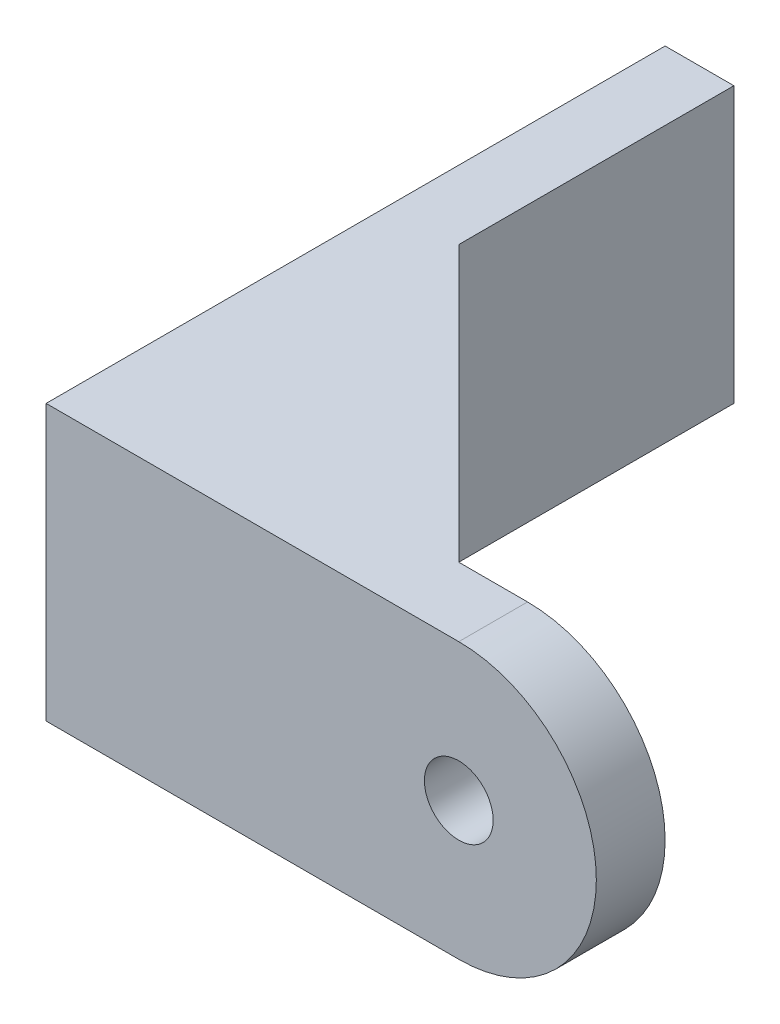
SolidWorks part; units mm, degrees
material "Custom Plastic"
ref_plane "Front Plane" through (0, 0, 0) normal (0, 0, 1) x (1, 0, 0)
ref_plane "Top Plane" through (0, 0, 0) normal (0, 1, 0) x (1, 0, 0)
ref_plane "Right Plane" through (0, 0, 0) normal (1, 0, 0) x (0, 0, -1)
sketch "Sketch1" plane through (0, 0, 0) normal (0, 0, 1) x (1, 0, 0)
  line L0 (-15, -10) -> (-15, 10)
  line L1 (-15, -10) -> (15, -10)
  line L2 (-15, 10) -> (15, 10)
  line L4 (0, 10) -> (0, -10) construction
  line L5 (-15, 0) -> (15, 0) construction
  line L6 (15, 0) -> (15, -10)
  arc A0 (15, 10) -> (15, -10) centre (15, 0) cw
  circle A1 centre (15, 0) radius 2.5
  point P1 (0, 0)
  dimension "D3" = 5
  dimension "D1" = 20
  dimension "D2" = 30
extrude "Boss-Extrude1" add sketch "Sketch1" along normal blind 5
sketch "Sketch2" plane through (0, 0, 0) normal (0, 0, -1) x (-1, 0, 0)
  line L0 (10, 10) -> (10, -10)
  line L3 (-15, -10) -> (15, -10)
  line L4 (15, -10) -> (15, 10)
  line L5 (15, 10) -> (-15, 10)
  line L6 (-15, -10) -> (15, -10)
  line L7 (15, -10) -> (15, 10)
  line L8 (15, 10) -> (-15, 10)
  arc A1 (-15, 10) -> (-15, -10) centre (-15, 0) ccw
  arc A2 (-15, 10) -> (-15, -10) centre (-15, 0) ccw
  line M6 (-15, -10) -> (15, -10)
  line M7 (15, -10) -> (15, 10)
  line M8 (15, 10) -> (-15, 10)
  dimension "D2" = 5
  dimension "D1" = 0
extrude "Boss-Extrude2" add sketch "Sketch2" along normal blind 40 contours L0 M8 M6 M7
sketch "Sketch4" plane through (0, -10, 0) normal (0, -1, 0) x (1, 0, 0)
  line L0 (10, 0) -> (-10, -20)
  line L6 (-15, 5) -> (-15, -40)
  line L7 (-15, -40) -> (-10, -40)
  line L8 (-10, -40) -> (-10, 0)
  line L9 (-10, 0) -> (15, 0)
  line L10 (15, 0) -> (15, 5)
  line L11 (15, 5) -> (-15, 5)
  line L12 (-15, 5) -> (-15, -40)
  line L13 (-15, -40) -> (-10, -40)
  line L14 (-10, -40) -> (-10, 0)
  line L15 (-10, 0) -> (15, 0)
  line L16 (15, 0) -> (15, 5)
  line L17 (15, 5) -> (-15, 5)
  dimension "D2" = 5
  dimension "D3" = 45
  dimension "D1" = 0
extrude "Boss-Extrude3" add sketch "Sketch4" against normal blind 5
sketch "Sketch5" plane through (0, 10, 0) normal (0, 1, 0) x (1, 0, 0)
  line L3 (10, 0) -> (-10, 20)
  line L4 (-10, 20) -> (-10, 0)
  line L5 (-10, 0) -> (10, 0)
  line L6 (10, 0) -> (-10, 20)
  line L7 (-10, 20) -> (-10, 0)
  line L8 (-10, 0) -> (10, 0)
  dimension "D1" = 0
extrude "Boss-Extrude4" add sketch "Sketch5" against normal blind 5
